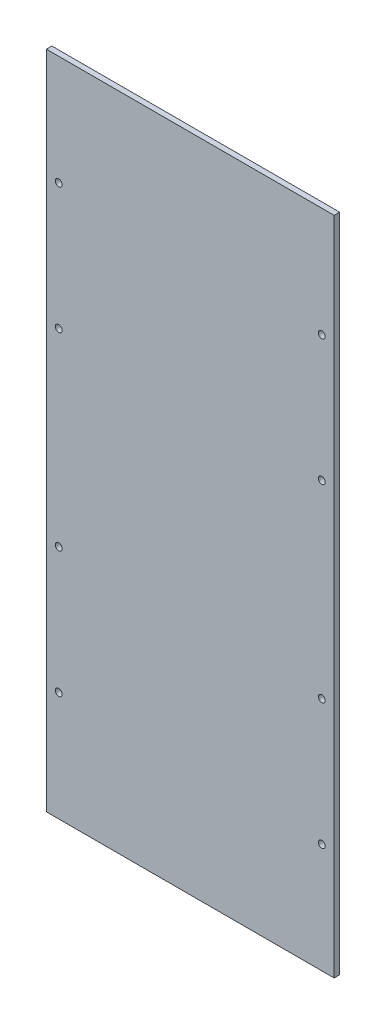
SolidWorks part; units mm, degrees
ref_plane "Alzado" through (0, 0, 0) normal (0, 0, 1) x (1, 0, 0)
ref_plane "Planta" through (0, 0, 0) normal (0, 1, 0) x (1, 0, 0)
ref_plane "Vista lateral" through (0, 0, 0) normal (1, 0, 0) x (0, 0, -1)
sketch "Croquis1" plane through (0, 0, 0) normal (0, 0, 1) x (1, 0, 0)
  line L1 (-90.5016, 703.6284) -> (119.4984, 703.6284)
  line L2 (-90.5016, 703.6284) -> (-90.5016, 1185.6284)
  line L3 (-90.5016, 1185.6284) -> (119.4984, 1185.6284)
  line L4 (119.4984, 703.6284) -> (119.4984, 1185.6284)
  circle A0 centre (110.4984, 1105.6384) radius 2.5
  circle A1 centre (-81.5016, 1105.6384) radius 2.5
  circle A2 centre (-81.5016, 1013.6384) radius 2.5
  circle A3 centre (110.4984, 1013.6384) radius 2.5
  circle A4 centre (-81.5016, 875.6184) radius 2.5
  circle A5 centre (110.4984, 783.6184) radius 2.5
  circle A6 centre (-81.5016, 783.6184) radius 2.5
  circle A7 centre (110.4984, 875.6184) radius 2.5
  dimension "D1" = 210
extrude "Saliente-Extruir1" add sketch "Croquis1" along normal blind 4
